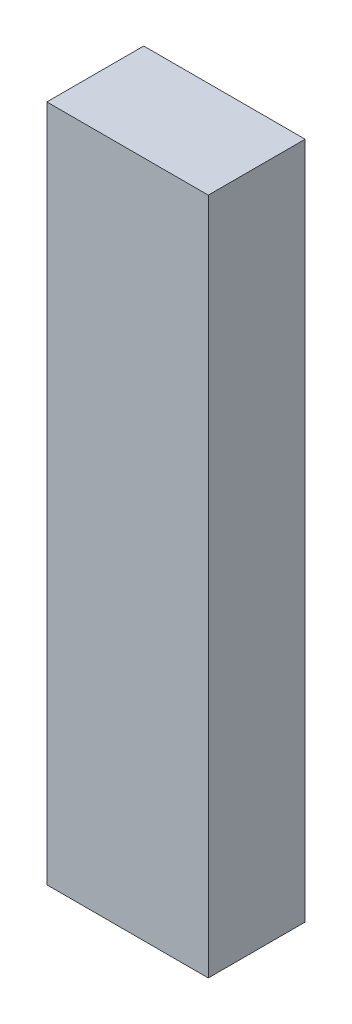
SolidWorks part; units mm, degrees
ref_plane "Front Plane" through (0, 0, 0) normal (0, 0, 1) x (1, 0, 0)
ref_plane "Top Plane" through (0, 0, 0) normal (0, 1, 0) x (1, 0, 0)
ref_plane "Right Plane" through (0, 0, 0) normal (1, 0, 0) x (0, 0, -1)
sketch "Sketch1" plane through (0, 0, 0) normal (0, 0, 1) x (1, 0, 0)
  line L1 (0, 0) -> (12.7, 0)
  line L2 (0, 0) -> (0, 53.34)
  line L3 (0, 53.34) -> (12.7, 53.34)
  line L4 (12.7, 0) -> (12.7, 53.34)
  dimension "D1" = 53.34
  dimension "D2" = 12.7
extrude "Boss-Extrude1" add sketch "Sketch1" along normal blind 7.62
equation "\"Foamcore\" = .1in"
equation "\"MDF\" = .3in"
equation "\"Gmaterial\"= \"MDF\""
equation "\"D1@Boss-Extrude1\"=\"Gmaterial\""
equation "\"D1@Sketch1\"=1.5+2*\"Gmaterial\""
